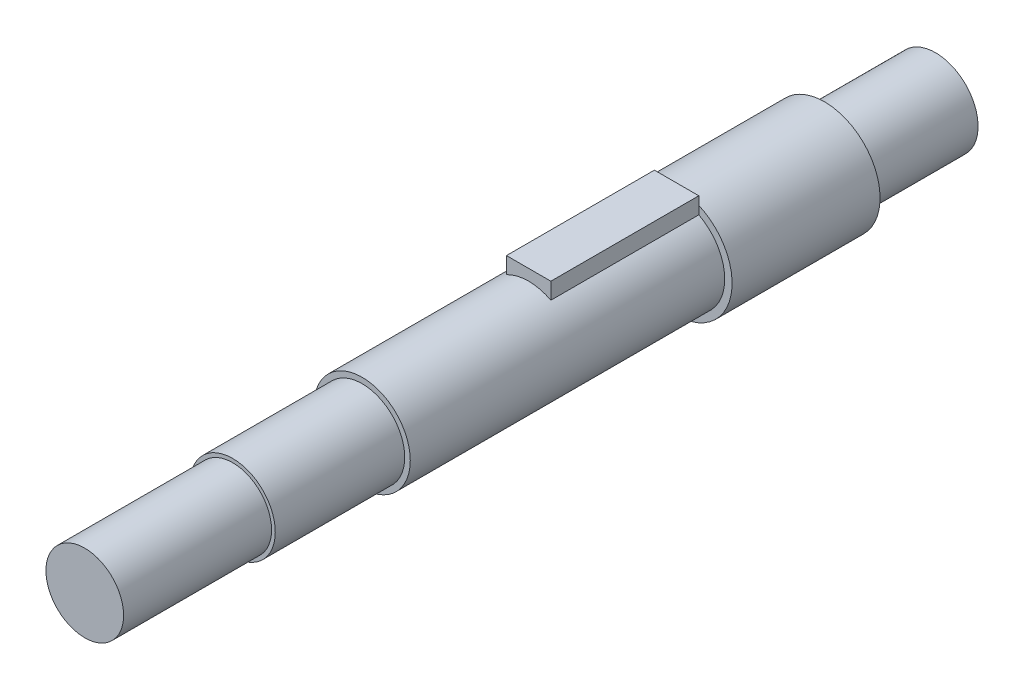
SolidWorks part; units mm, degrees
ref_plane "Front Plane" through (0, 0, 0) normal (0, 0, 1) x (1, 0, 0)
ref_plane "Top Plane" through (0, 0, 0) normal (0, 1, 0) x (1, 0, 0)
ref_plane "Right Plane" through (0, 0, 0) normal (1, 0, 0) x (0, 0, -1)
sketch "Sketch2" plane through (0, 0, 0) normal (0, 0, 1) x (1, 0, 0)
  circle A0 centre (0, 0) radius 15
  dimension "D1" = 30
extrude "Boss-Extrude1" add sketch "Sketch2" along normal blind 230
sketch "Sketch3" plane through (0, 0, 230) normal (0, 0, 1) x (1, 0, 0)
  circle A0 centre (0, 0) radius 13
  circle A1 centre (0, 0) radius 11.5
  circle A2 centre (0, 0) radius 10.5
  circle M1 centre (0, 0) radius 15
  dimension "D1" = 26
  dimension "D2" = 23
  dimension "D3" = 21
extrude "Cut-Extrude1" cut sketch "Sketch3" against normal blind 160 contours A0 M1
sketch "Sketch4" plane through (0, 0, 230) normal (0, 0, 1) x (1, 0, 0)
  circle A0 centre (0, 0) radius 11.5
  circle A1 centre (0, 0) radius 13
  dimension "D1" = 23
  dimension "D2" = 26
extrude "Cut-Extrude3" cut sketch "Sketch4" against normal blind 75 contours A1 | A0
sketch "Sketch5" plane through (0, 0, 230) normal (0, 0, 1) x (1, 0, 0)
  circle A0 centre (0, 0) radius 11.5
  circle A1 centre (0, 0) radius 10.5
  dimension "D1" = 21
  dimension "D2" = 23
extrude "Cut-Extrude4" cut sketch "Sketch5" against normal blind 40
sketch "Sketch6" plane through (0, 0, 0) normal (0, 0, -1) x (-1, 0, 0)
  line L0 (0, 16.5) -> (0, -16.5) construction
  circle A0 centre (0, 0) radius 15
  circle A1 centre (0, 0) radius 11.5
  circle A2 centre (0, 0) radius 15 construction
  dimension "D1" = 23
  dimension "D2" = 30
extrude "Cut-Extrude5" cut sketch "Sketch6" against normal blind 30
sketch "Sketch8" plane through (0, 0, 70) normal (0, 0, 1) x (1, 0, 0)
  line L0 (0, 0) -> (0, 21.1222) construction
  line L2 (-6, 16) -> (6, 16)
  line L3 (-6, 16) -> (-6, 11.5326)
  line L5 (6, 16) -> (6, 11.5326)
  line L6 (-6, 16) -> (6, 10) construction
  line L7 (-6, 10) -> (6, 16) construction
  circle A0 centre (0, 0) radius 13 construction
  arc A1 (6, 11.5326) -> (-6, 11.5326) centre (0, 0) ccw
  point P3 (0, 13)
  dimension "D1" = 26
  dimension "D2" = 6
  dimension "D3" = 12
  dimension "D4" = 4.4674
  dimension "D5" = 12
extrude "Boss-Extrude2" add sketch "Sketch8" along normal blind 40
